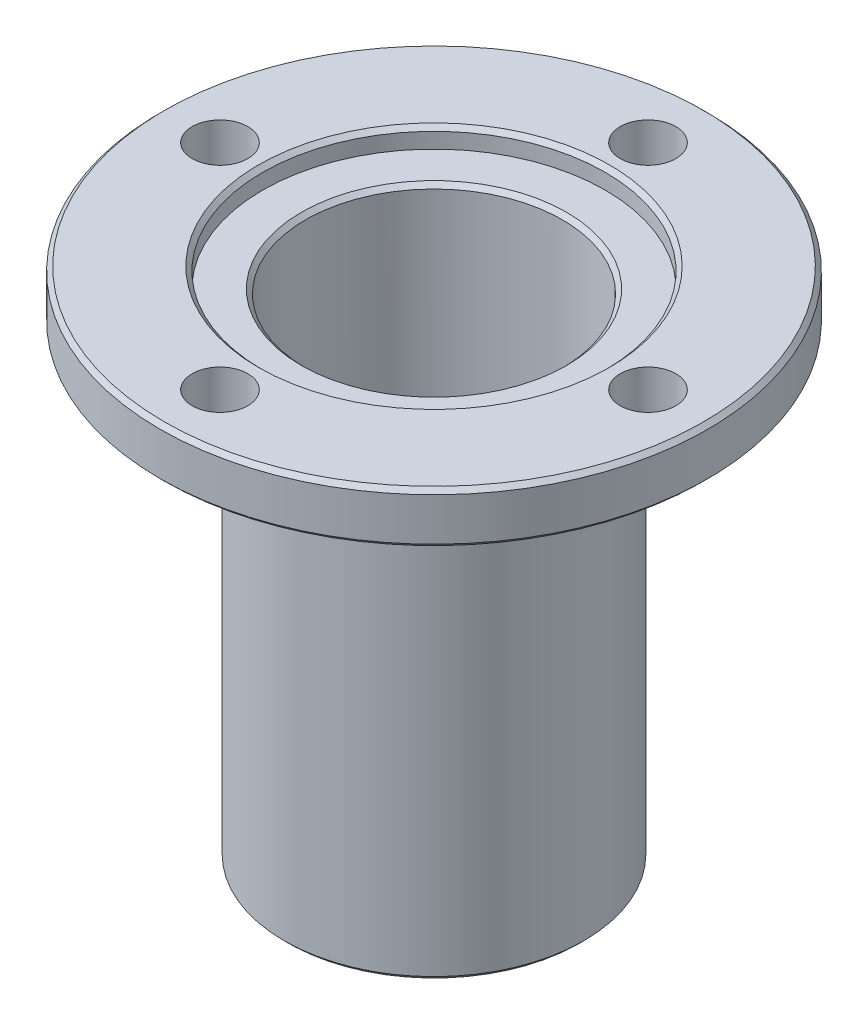
SolidWorks part; units mm, degrees
ref_plane "Front Plane" through (0, 0, 0) normal (0, 0, 1) x (1, 0, 0)
ref_plane "Top Plane" through (0, 0, 0) normal (0, 1, 0) x (1, 0, 0)
ref_plane "Right Plane" through (0, 0, 0) normal (1, 0, 0) x (0, 0, -1)
sketch "Sketch1" plane through (0, 0, 0) normal (0, 1, 0) x (1, 0, 0)
  circle A0 centre (0, 0) radius 32
  dimension "D1" = 64
extrude "Boss-Extrude1" add sketch "Sketch1" along normal blind 6
sketch "Sketch2" plane through (0, 0, 0) normal (0, -1, 0) x (1, 0, 0)
  circle A0 centre (0, 0) radius 17.5
  dimension "D1" = 35
extrude "Boss-Extrude2" add sketch "Sketch2" along normal blind 54
sketch "Sketch3" plane through (0, 6, 0) normal (0, 1, 0) x (1, 0, 0)
  circle A0 centre (0, 0) radius 20
  dimension "D1" = 40
extrude "Cut-Extrude1" cut sketch "Sketch3" against normal blind 2.3
sketch "Sketch4" plane through (0, 3.7, 0) normal (0, 1, 0) x (1, 0, 0)
  circle A0 centre (0, 0) radius 15
  dimension "D1" = 30
extrude "Cut-Extrude2" cut sketch "Sketch4" against normal through all
sketch "Sketch5" plane through (0, 6, 0) normal (0, 1, 0) x (1, 0, 0)
  circle A0 centre (0, 0) radius 25 construction
  circle A1 centre (0, 25) radius 3.25
  circle A2 centre (25, 0) radius 3.25
  circle A3 centre (0, -25) radius 3.25
  circle A4 centre (-25, 0) radius 3.25
  dimension "D1" = 50
  dimension "D2" = 6.5
extrude "Cut-Extrude3" cut sketch "Sketch5" against normal through all
chamfer "Chamfer1" distance 0.5 angle 45 6 edges at (0, -54, -17.5) (0, -54, 15) (0, 3.7, 15) (0, 6, 20) (0, 0, 32) (0, 6, 32)
